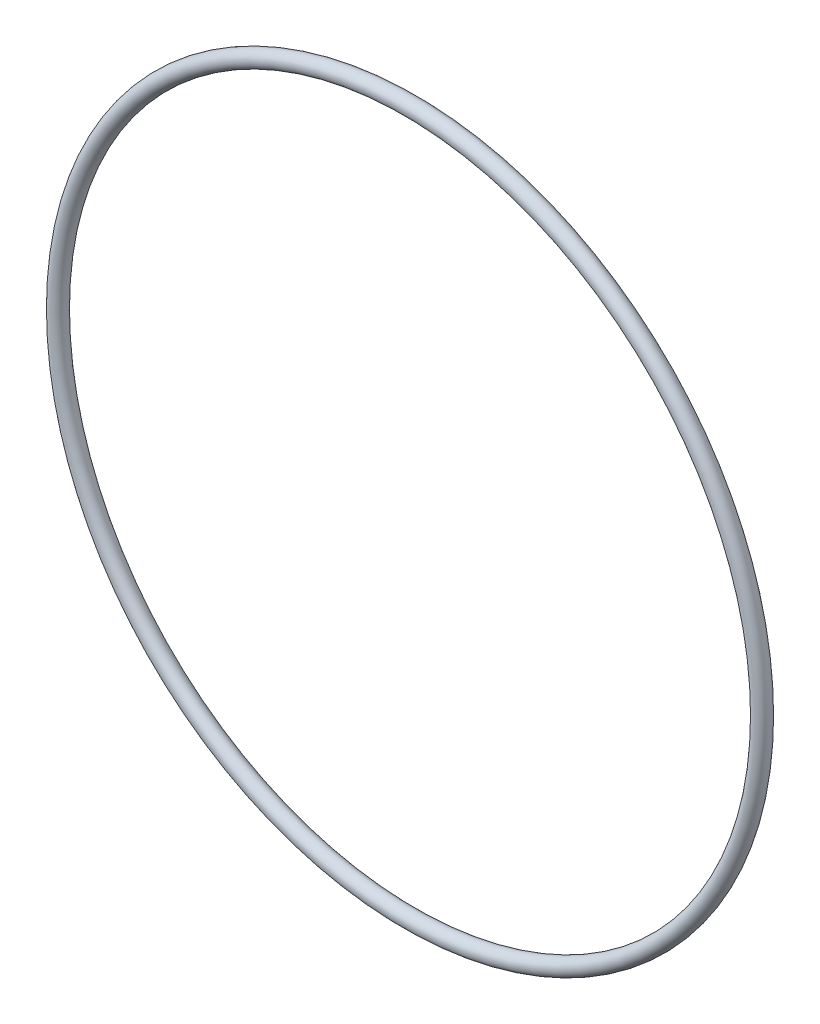
SolidWorks part; units mm, degrees
ref_plane "Front" through (0, 0, 0) normal (0, 0, 1) x (1, 0, 0)
ref_plane "Top" through (0, 0, 0) normal (0, 1, 0) x (1, 0, 0)
ref_plane "Right" through (0, 0, 0) normal (1, 0, 0) x (0, 0, -1)
sketch "Sketch1" plane through (0, 0, 0) normal (1, 0, 0) x (0, -1, 0)
  line L0 (0, -1.7653) -> (0, 1.7653) construction
  line L2 (-85.7339, 0) -> (85.7339, 0) construction
  line L3 (-74.4093, 0) -> (74.4093, 0) construction
  circle A0 centre (76.1746, 0) radius 1.7653
  point P9 (74.4093, 0)
  point P10 (77.9399, 0)
  point P13 (76.1746, 1.7653)
  point P14 (76.1746, -1.7653)
  dimension "Width" = 3.5306
  dimension "ID" = 148.8186
revolve "Revolve1" add sketch "Sketch1" angle 360 about L0
